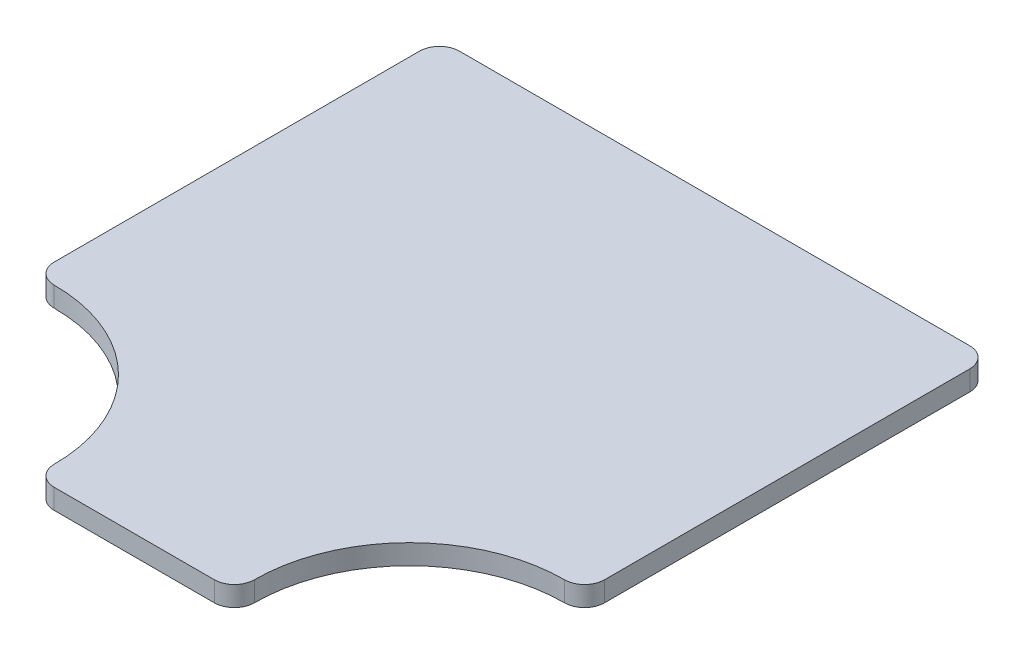
SolidWorks part; units mm, degrees
ref_plane "Alzado" through (0, 0, 0) normal (0, 0, 1) x (1, 0, 0)
ref_plane "Planta" through (0, 0, 0) normal (0, 1, 0) x (1, 0, 0)
ref_plane "Vista lateral" through (0, 0, 0) normal (1, 0, 0) x (0, 0, -1)
sketch "Croquis1" plane through (0, 0, 0) normal (0, 1, 0) x (1, 0, 0)
  line L9 (-41.5284, 41.1922) -> (9.4716, 41.1922)
  line L10 (-43.5284, 39.1922) -> (-43.5284, 2.6922)
  line L11 (-24.0284, -16.8078) -> (-8.0284, -16.8078)
  line L12 (11.4716, 39.1922) -> (11.4716, 2.6922)
  arc A5 (-26.0284, -14.8078) -> (-41.5284, 0.6922) centre (-41.5284, -14.8078) ccw
  arc A7 (9.4716, 0.6922) -> (-6.0284, -14.8078) centre (9.4716, -14.8078) ccw
  arc A9 (-43.5284, 2.6922) -> (-41.5284, 0.6922) centre (-41.5284, 2.6922) ccw
  arc A11 (-26.0284, -14.8078) -> (-24.0284, -16.8078) centre (-24.0284, -14.8078) ccw
  arc A12 (-6.0284, -14.8078) -> (-8.0284, -16.8078) centre (-8.0284, -14.8078) cw
  arc A14 (11.4716, 2.6922) -> (9.4716, 0.6922) centre (9.4716, 2.6922) cw
  arc A16 (11.4716, 39.1922) -> (9.4716, 41.1922) centre (9.4716, 39.1922) ccw
  arc A17 (-41.5284, 41.1922) -> (-43.5284, 39.1922) centre (-41.5284, 39.1922) ccw
  dimension "D13" = 31
  dimension "D15" = 31
extrude "Saliente-Extruir1" add sketch "Croquis1" along normal blind 2
